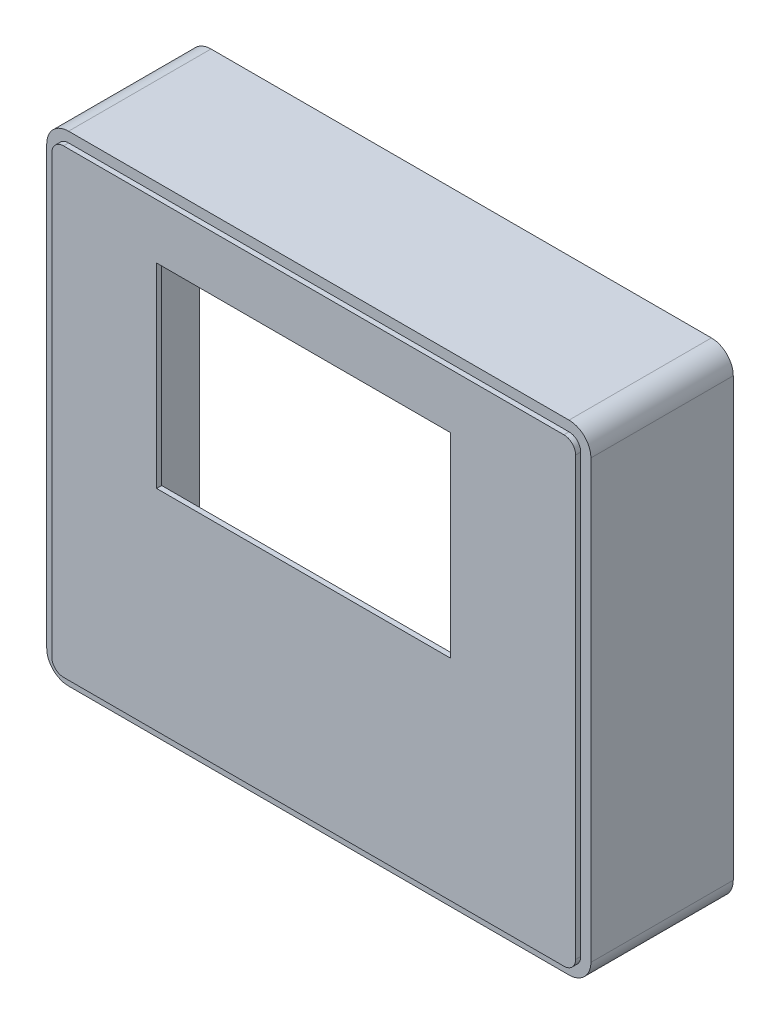
SolidWorks part; units mm, degrees
ref_plane "Front Plane" through (0, 0, 0) normal (0, 0, 1) x (1, 0, 0)
ref_plane "Top Plane" through (0, 0, 0) normal (0, 1, 0) x (1, 0, 0)
ref_plane "Right Plane" through (0, 0, 0) normal (1, 0, 0) x (0, 0, -1)
sketch "Sketch2" plane through (0, 0, 0) normal (0, 0, 1) x (1, 0, 0)
  line L4 (-18.7, 47.45) -> (-18.7, -38.45)
  line L5 (-14.4, -42.75) -> (84, -42.75)
  line L6 (88.3, -38.45) -> (88.3, 47.45)
  line L7 (84, 51.75) -> (-14.4, 51.75)
  line L8 (84, 49.75) -> (-14.4, 49.75)
  line L9 (-16.7, 47.45) -> (-16.7, -38.45)
  line L10 (-14.4, -40.75) -> (84, -40.75)
  line L11 (86.3, -38.45) -> (86.3, 47.45)
  line L12 (84, 49.75) -> (-14.4, 49.75)
  line L13 (-16.7, 47.45) -> (-16.7, -38.45)
  line L14 (-14.4, -40.75) -> (84, -40.75)
  line L15 (86.3, -38.45) -> (86.3, 47.45)
  arc A4 (-18.7, -38.45) -> (-14.4, -42.75) centre (-14.4, -38.45) ccw
  arc A5 (84, -42.75) -> (88.3, -38.45) centre (84, -38.45) ccw
  arc A6 (88.3, 47.45) -> (84, 51.75) centre (84, 47.45) ccw
  arc A7 (-14.4, 51.75) -> (-18.7, 47.45) centre (-14.4, 47.45) ccw
  arc A8 (86.3, 47.45) -> (84, 49.75) centre (84, 47.45) ccw
  arc A9 (-14.4, 49.75) -> (-16.7, 47.45) centre (-14.4, 47.45) ccw
  arc A10 (-16.7, -38.45) -> (-14.4, -40.75) centre (-14.4, -38.45) ccw
  arc A11 (84, -40.75) -> (86.3, -38.45) centre (84, -38.45) ccw
  arc A12 (86.3, 47.45) -> (84, 49.75) centre (84, 47.45) ccw
  arc A13 (-14.4, 49.75) -> (-16.7, 47.45) centre (-14.4, 47.45) ccw
  arc A14 (-16.7, -38.45) -> (-14.4, -40.75) centre (-14.4, -38.45) ccw
  arc A15 (84, -40.75) -> (86.3, -38.45) centre (84, -38.45) ccw
  dimension "D1" = 2
  dimension "D2" = 2
extrude "Boss-Extrude1" add sketch "Sketch2" along normal blind 28
sketch "Sketch3" plane through (0, 0, 0) normal (0, 0, 1) x (1, 0, 0)
  line L4 (61.7, 0.56) -> (61.7, 38.96)
  line L5 (61.7, 38.96) -> (3.9, 38.96)
  line L6 (3.9, 38.96) -> (3.9, 0.56)
  line L7 (3.9, 0.56) -> (61.7, 0.56)
  line L8 (61.7, 0.56) -> (61.7, 38.96)
  line L9 (61.7, 38.96) -> (3.9, 38.96)
  line L10 (3.9, 38.96) -> (3.9, 0.56)
  line L11 (3.9, 0.56) -> (61.7, 0.56)
  line L12 (-18.7, 47.45) -> (-18.7, -38.45)
  line L13 (-14.4, -42.75) -> (84, -42.75)
  line L14 (88.3, -38.45) -> (88.3, 47.45)
  line L15 (84, 51.75) -> (-14.4, 51.75)
  line L16 (-18.7, 47.45) -> (-18.7, -38.45)
  line L17 (-14.4, -42.75) -> (84, -42.75)
  line L18 (88.3, -38.45) -> (88.3, 47.45)
  line L19 (84, 51.75) -> (-14.4, 51.75)
  arc A4 (-14.4, 51.75) -> (-18.7, 47.45) centre (-14.4, 47.45) ccw
  arc A5 (-18.7, -38.45) -> (-14.4, -42.75) centre (-14.4, -38.45) ccw
  arc A6 (84, -42.75) -> (88.3, -38.45) centre (84, -38.45) ccw
  arc A7 (88.3, 47.45) -> (84, 51.75) centre (84, 47.45) ccw
  arc A8 (-14.4, 51.75) -> (-18.7, 47.45) centre (-14.4, 47.45) ccw
  arc A9 (-18.7, -38.45) -> (-14.4, -42.75) centre (-14.4, -38.45) ccw
  arc A10 (84, -42.75) -> (88.3, -38.45) centre (84, -38.45) ccw
  arc A11 (88.3, 47.45) -> (84, 51.75) centre (84, 47.45) ccw
  dimension "D1" = 0
  dimension "D2" = 0
extrude "Boss-Extrude2" add sketch "Sketch3" along normal blind 28
sketch "Sketch4" plane through (0, -42.75, 0) normal (0, -1, 0) x (1, 0, 0)
  line L0 (72.33, 3.4762) -> (72.33, 0.0462) construction
  line L1 (72.33, 0.0462) -> (81.22, 0.0462) construction
  line L2 (81.22, 0.0462) -> (81.22, 3.4762) construction
  line L3 (81.22, 3.4762) -> (72.33, 3.4762) construction
  line L4 (-13.85, 10.97) -> (-13.85, -0.03)
  line L5 (-13.85, -0.03) -> (-4.55, -0.03)
  line L6 (-4.55, -0.03) -> (-4.55, 10.97)
  line L7 (-4.55, 10.97) -> (-13.85, 10.97)
  line L8 (-13.85, 10.97) -> (-13.85, -0.03)
  line L9 (-13.85, -0.03) -> (-4.55, -0.03)
  line L10 (-4.55, -0.03) -> (-4.55, 10.97)
  line L11 (-4.55, 10.97) -> (-13.85, 10.97)
  line L12 (-1.288, 6.8562) -> (-1.288, 0.0462)
  line L13 (-1.288, 0.0462) -> (16.408, 0.0462)
  line L14 (16.408, 0.0462) -> (16.408, 6.8562)
  line L15 (16.408, 6.8562) -> (-1.288, 6.8562)
  line L16 (-1.288, 6.8562) -> (-1.288, 0.0462)
  line L17 (-1.288, 0.0462) -> (16.408, 0.0462)
  line L18 (16.408, 0.0462) -> (16.408, 6.8562)
  line L19 (16.408, 6.8562) -> (-1.288, 6.8562)
  line L20 (66.12, -0.03) -> (68.12, -0.03) construction
  line L21 (68.12, 13.62) -> (66.12, 13.62) construction
  line L22 (68.12, -0.03) -> (69.827, -0.03) construction
  line L23 (69.827, -0.03) -> (69.827, 13.62) construction
  line L24 (69.827, 13.62) -> (68.12, 13.62) construction
  line L25 (57.38, -0.03) -> (66.12, -0.03) construction
  line L26 (66.12, 13.62) -> (57.38, 13.62) construction
  line L27 (55.38, -0.03) -> (57.38, -0.03) construction
  line L28 (57.38, 13.62) -> (55.38, 13.62) construction
  line L29 (53.673, 13.62) -> (53.673, -0.03) construction
  line L30 (53.673, -0.03) -> (55.38, -0.03) construction
  line L31 (55.38, 13.62) -> (53.673, 13.62) construction
  line L32 (37.375, 16.8862) -> (37.375, 0.0462) construction
  line L33 (37.375, 0.0462) -> (51.425, 0.0462) construction
  line L34 (51.425, 0.0462) -> (51.425, 16.8862) construction
  line L35 (51.425, 16.8862) -> (37.375, 16.8862) construction
  line L36 (20.375, 16.8862) -> (20.375, 0.0462) construction
  line L37 (20.375, 0.0462) -> (34.425, 0.0462) construction
  line L38 (34.425, 0.0462) -> (34.425, 16.8862) construction
  line L39 (34.425, 16.8862) -> (20.375, 16.8862) construction
  line L40 (72.33, 3.4762) -> (72.33, 0.0462)
  line L41 (72.33, 0.0462) -> (81.22, 0.0462)
  line L42 (81.22, 0.0462) -> (81.22, 3.4762)
  line L43 (81.22, 3.4762) -> (72.33, 3.4762)
  line L44 (66.12, -0.03) -> (68.12, -0.03)
  line L45 (68.12, 13.62) -> (66.12, 13.62)
  line L46 (68.12, -0.03) -> (69.827, -0.03)
  line L47 (69.827, -0.03) -> (69.827, 13.62)
  line L48 (69.827, 13.62) -> (68.12, 13.62)
  line L49 (57.38, -0.03) -> (66.12, -0.03)
  line L50 (66.12, 13.62) -> (57.38, 13.62)
  line L51 (55.38, -0.03) -> (57.38, -0.03)
  line L52 (57.38, 13.62) -> (55.38, 13.62)
  line L53 (53.673, 13.62) -> (53.673, -0.03)
  line L54 (53.673, -0.03) -> (55.38, -0.03)
  line L55 (55.38, 13.62) -> (53.673, 13.62)
  line L56 (37.375, 16.8862) -> (37.375, 0.0462)
  line L57 (37.375, 0.0462) -> (51.425, 0.0462)
  line L58 (51.425, 0.0462) -> (51.425, 16.8862)
  line L59 (51.425, 16.8862) -> (37.375, 16.8862)
  line L60 (20.375, 16.8862) -> (20.375, 0.0462)
  line L61 (20.375, 0.0462) -> (34.425, 0.0462)
  line L62 (34.425, 0.0462) -> (34.425, 16.8862)
  line L63 (34.425, 16.8862) -> (20.375, 16.8862)
  dimension "D1" = 0
  dimension "D2" = 0
extrude "Cut-Extrude1" cut sketch "Sketch4" against normal blind 2
sketch "Sketch5" plane through (-18.7, 0, 0) normal (-1, 0, 0) x (0, 0, 1)
  line L0 (26.466, 1.76) -> (26.466, 4.86) construction
  line L1 (14.266, 4.86) -> (14.266, 1.76) construction
  line L2 (26.166, 5.16) -> (14.566, 5.16) construction
  line L3 (26.166, 1.46) -> (14.566, 1.46) construction
  line L4 (26.466, 1.76) -> (26.466, 4.86)
  line L5 (14.266, 4.86) -> (14.266, 1.76)
  line L6 (26.166, 5.16) -> (14.566, 5.16)
  line L7 (26.166, 1.46) -> (14.566, 1.46)
  line L8 (26.166, 9.86) -> (14.566, 9.86)
  line L9 (14.266, 9.56) -> (14.266, 6.46)
  line L10 (26.166, 6.16) -> (14.566, 6.16)
  line L11 (26.466, 6.46) -> (26.466, 9.56)
  line L12 (26.166, 14.56) -> (14.566, 14.56)
  line L13 (14.266, 14.26) -> (14.266, 11.16)
  line L14 (26.166, 10.86) -> (14.566, 10.86)
  line L15 (26.466, 11.16) -> (26.466, 14.26)
  line L16 (26.166, 19.26) -> (14.566, 19.26)
  line L17 (14.266, 18.96) -> (14.266, 15.86)
  line L18 (26.166, 15.56) -> (14.566, 15.56)
  line L19 (26.466, 15.86) -> (26.466, 18.96)
  line L20 (26.166, 23.96) -> (14.566, 23.96)
  line L21 (14.266, 23.66) -> (14.266, 20.56)
  line L22 (26.166, 20.26) -> (14.566, 20.26)
  line L23 (26.466, 20.56) -> (26.466, 23.66)
  line L24 (26.166, 28.66) -> (14.566, 28.66)
  line L25 (14.266, 28.36) -> (14.266, 25.26)
  line L26 (26.166, 24.96) -> (14.566, 24.96)
  line L27 (26.466, 25.26) -> (26.466, 28.36)
  line L28 (26.166, 33.36) -> (14.566, 33.36)
  line L29 (14.266, 33.06) -> (14.266, 29.96)
  line L30 (26.166, 29.66) -> (14.566, 29.66)
  line L31 (26.466, 29.96) -> (26.466, 33.06)
  line L32 (26.166, 38.06) -> (14.566, 38.06)
  line L33 (14.266, 37.76) -> (14.266, 34.66)
  line L34 (26.166, 34.36) -> (14.566, 34.36)
  line L35 (26.466, 34.66) -> (26.466, 37.76)
  arc A0 (26.466, 4.86) -> (26.166, 5.16) centre (26.166, 4.86) ccw construction
  arc A1 (26.166, 1.46) -> (26.466, 1.76) centre (26.166, 1.76) ccw construction
  arc A2 (14.266, 1.76) -> (14.566, 1.46) centre (14.566, 1.76) ccw construction
  arc A3 (14.566, 5.16) -> (14.266, 4.86) centre (14.566, 4.86) ccw construction
  arc A4 (26.466, 4.86) -> (26.166, 5.16) centre (26.166, 4.86) ccw
  arc A5 (26.166, 1.46) -> (26.466, 1.76) centre (26.166, 1.76) ccw
  arc A6 (14.266, 1.76) -> (14.566, 1.46) centre (14.566, 1.76) ccw
  arc A7 (14.566, 5.16) -> (14.266, 4.86) centre (14.566, 4.86) ccw
  arc A8 (26.466, 9.56) -> (26.166, 9.86) centre (26.166, 9.56) ccw
  arc A9 (14.566, 9.86) -> (14.266, 9.56) centre (14.566, 9.56) ccw
  arc A10 (14.266, 6.46) -> (14.566, 6.16) centre (14.566, 6.46) ccw
  arc A11 (26.166, 6.16) -> (26.466, 6.46) centre (26.166, 6.46) ccw
  arc A12 (26.466, 14.26) -> (26.166, 14.56) centre (26.166, 14.26) ccw
  arc A13 (14.566, 14.56) -> (14.266, 14.26) centre (14.566, 14.26) ccw
  arc A14 (14.266, 11.16) -> (14.566, 10.86) centre (14.566, 11.16) ccw
  arc A15 (26.166, 10.86) -> (26.466, 11.16) centre (26.166, 11.16) ccw
  arc A16 (26.466, 18.96) -> (26.166, 19.26) centre (26.166, 18.96) ccw
  arc A17 (14.566, 19.26) -> (14.266, 18.96) centre (14.566, 18.96) ccw
  arc A18 (14.266, 15.86) -> (14.566, 15.56) centre (14.566, 15.86) ccw
  arc A19 (26.166, 15.56) -> (26.466, 15.86) centre (26.166, 15.86) ccw
  arc A20 (26.466, 23.66) -> (26.166, 23.96) centre (26.166, 23.66) ccw
  arc A21 (14.566, 23.96) -> (14.266, 23.66) centre (14.566, 23.66) ccw
  arc A22 (14.266, 20.56) -> (14.566, 20.26) centre (14.566, 20.56) ccw
  arc A23 (26.166, 20.26) -> (26.466, 20.56) centre (26.166, 20.56) ccw
  arc A24 (26.466, 28.36) -> (26.166, 28.66) centre (26.166, 28.36) ccw
  arc A25 (14.566, 28.66) -> (14.266, 28.36) centre (14.566, 28.36) ccw
  arc A26 (14.266, 25.26) -> (14.566, 24.96) centre (14.566, 25.26) ccw
  arc A27 (26.166, 24.96) -> (26.466, 25.26) centre (26.166, 25.26) ccw
  arc A28 (26.466, 33.06) -> (26.166, 33.36) centre (26.166, 33.06) ccw
  arc A29 (14.566, 33.36) -> (14.266, 33.06) centre (14.566, 33.06) ccw
  arc A30 (14.266, 29.96) -> (14.566, 29.66) centre (14.566, 29.96) ccw
  arc A31 (26.166, 29.66) -> (26.466, 29.96) centre (26.166, 29.96) ccw
  arc A32 (26.466, 37.76) -> (26.166, 38.06) centre (26.166, 37.76) ccw
  arc A33 (14.566, 38.06) -> (14.266, 37.76) centre (14.566, 37.76) ccw
  arc A34 (14.266, 34.66) -> (14.566, 34.36) centre (14.566, 34.66) ccw
  arc A35 (26.166, 34.36) -> (26.466, 34.66) centre (26.166, 34.66) ccw
  dimension "D2" = 1
  dimension "D1" = 8
extrude "Cut-Extrude2" cut sketch "Sketch5" against normal blind 23
sketch "Sketch6" plane through (0, 0, 28) normal (0, 0, 1) x (1, 0, 0)
  line L0 (-16.7, 47.45) -> (-16.7, -38.45)
  line L1 (-14.4, -40.75) -> (84, -40.75)
  line L2 (86.3, -38.45) -> (86.3, 47.45)
  line L3 (84, 49.75) -> (-14.4, 49.75)
  line L4 (-18.7, 47.45) -> (-18.7, -38.45)
  line L5 (-14.4, -42.75) -> (84, -42.75)
  line L6 (88.3, -38.45) -> (88.3, 47.45)
  line L7 (84, 51.75) -> (-14.4, 51.75)
  line L8 (-18.7, 47.45) -> (-18.7, -38.45)
  line L9 (-14.4, -42.75) -> (84, -42.75)
  line L10 (88.3, -38.45) -> (88.3, 47.45)
  line L11 (84, 51.75) -> (-14.4, 51.75)
  line L16 (61.7, 0.56) -> (61.7, 38.96)
  line L17 (61.7, 38.96) -> (3.9, 38.96)
  line L18 (3.9, 38.96) -> (3.9, 0.56)
  line L19 (3.9, 0.56) -> (61.7, 0.56)
  line L20 (61.7, 0.56) -> (61.7, 38.96)
  line L21 (61.7, 38.96) -> (3.9, 38.96)
  line L22 (3.9, 38.96) -> (3.9, 0.56)
  line L23 (3.9, 0.56) -> (61.7, 0.56)
  arc A0 (-16.7, -38.45) -> (-14.4, -40.75) centre (-14.4, -38.45) ccw
  arc A1 (84, -40.75) -> (86.3, -38.45) centre (84, -38.45) ccw
  arc A2 (86.3, 47.45) -> (84, 49.75) centre (84, 47.45) ccw
  arc A3 (-14.4, 49.75) -> (-16.7, 47.45) centre (-14.4, 47.45) ccw
  arc A4 (-14.4, 51.75) -> (-18.7, 47.45) centre (-14.4, 47.45) ccw
  arc A5 (-18.7, -38.45) -> (-14.4, -42.75) centre (-14.4, -38.45) ccw
  arc A6 (84, -42.75) -> (88.3, -38.45) centre (84, -38.45) ccw
  arc A7 (88.3, 47.45) -> (84, 51.75) centre (84, 47.45) ccw
  arc A8 (-14.4, 51.75) -> (-18.7, 47.45) centre (-14.4, 47.45) ccw
  arc A9 (-18.7, -38.45) -> (-14.4, -42.75) centre (-14.4, -38.45) ccw
  arc A10 (84, -42.75) -> (88.3, -38.45) centre (84, -38.45) ccw
  arc A11 (88.3, 47.45) -> (84, 51.75) centre (84, 47.45) ccw
  line M17 (61.7, 38.96) -> (61.7, 0.56)
  line M18 (61.7, 0.56) -> (3.9, 0.56)
  line M19 (3.9, 0.56) -> (3.9, 38.96)
  line M20 (3.9, 38.96) -> (61.7, 38.96)
  dimension "D1" = 0
  dimension "D2" = 2
  dimension "D3" = 0
extrude "Cut-Extrude5" cut sketch "Sketch6" against normal blind 28 contours L3 A3 L0 A0 L1 A1 L2 A2 M20 M17 M18 M19
sketch "Sketch7" plane through (0, 0, 28) normal (0, 0, 1) x (1, 0, 0)
  line L24 (86.3, -38.45) -> (86.3, 47.45)
  line L25 (-14.4, -40.75) -> (84, -40.75)
  line L26 (-16.7, 47.45) -> (-16.7, -38.45)
  line L27 (84, 49.75) -> (-14.4, 49.75)
  line L28 (86.3, -38.45) -> (86.3, 47.45)
  line L29 (-14.4, -40.75) -> (84, -40.75)
  line L30 (-16.7, 47.45) -> (-16.7, -38.45)
  line L31 (84, 49.75) -> (-14.4, 49.75)
  line L32 (61.7, 0.56) -> (61.7, 38.96)
  line L33 (61.7, 38.96) -> (3.9, 38.96)
  line L34 (3.9, 38.96) -> (3.9, 0.56)
  line L35 (3.9, 0.56) -> (61.7, 0.56)
  line L36 (61.7, 0.56) -> (61.7, 38.96)
  line L37 (61.7, 38.96) -> (3.9, 38.96)
  line L38 (3.9, 38.96) -> (3.9, 0.56)
  line L39 (3.9, 0.56) -> (61.7, 0.56)
  arc A20 (86.3, 47.45) -> (84, 49.75) centre (84, 47.45) ccw
  arc A21 (84, -40.75) -> (86.3, -38.45) centre (84, -38.45) ccw
  arc A22 (-16.7, -38.45) -> (-14.4, -40.75) centre (-14.4, -38.45) ccw
  arc A23 (-14.4, 49.75) -> (-16.7, 47.45) centre (-14.4, 47.45) ccw
  arc A24 (86.3, 47.45) -> (84, 49.75) centre (84, 47.45) ccw
  arc A25 (84, -40.75) -> (86.3, -38.45) centre (84, -38.45) ccw
  arc A26 (-16.7, -38.45) -> (-14.4, -40.75) centre (-14.4, -38.45) ccw
  arc A27 (-14.4, 49.75) -> (-16.7, 47.45) centre (-14.4, 47.45) ccw
  dimension "D1" = 2
  dimension "D2" = 0
extrude "Boss-Extrude3" add sketch "Sketch7" along normal blind 28 separate body
sketch "Sketch8" plane through (0, 0, 56) normal (0, 0, 1) x (1, 0, 0)
  line L4 (84, 49.75) -> (-14.4, 49.75)
  line L5 (-16.7, 47.45) -> (-16.7, -38.45)
  line L6 (-14.4, -40.75) -> (84, -40.75)
  line L7 (86.3, -38.45) -> (86.3, 47.45)
  line L8 (84, 49.75) -> (-14.4, 49.75)
  line L9 (-16.7, 47.45) -> (-16.7, -38.45)
  line L10 (-14.4, -40.75) -> (84, -40.75)
  line L11 (86.3, -38.45) -> (86.3, 47.45)
  arc A4 (86.3, 47.45) -> (84, 49.75) centre (84, 47.45) ccw
  arc A5 (-14.4, 49.75) -> (-16.7, 47.45) centre (-14.4, 47.45) ccw
  arc A6 (-16.7, -38.45) -> (-14.4, -40.75) centre (-14.4, -38.45) ccw
  arc A7 (84, -40.75) -> (86.3, -38.45) centre (84, -38.45) ccw
  arc A8 (86.3, 47.45) -> (84, 49.75) centre (84, 47.45) ccw
  arc A9 (-14.4, 49.75) -> (-16.7, 47.45) centre (-14.4, 47.45) ccw
  arc A10 (-16.7, -38.45) -> (-14.4, -40.75) centre (-14.4, -38.45) ccw
  arc A11 (84, -40.75) -> (86.3, -38.45) centre (84, -38.45) ccw
  dimension "D1" = 0
extrude "Cut-Extrude7" cut sketch "Sketch8" against normal blind 27
